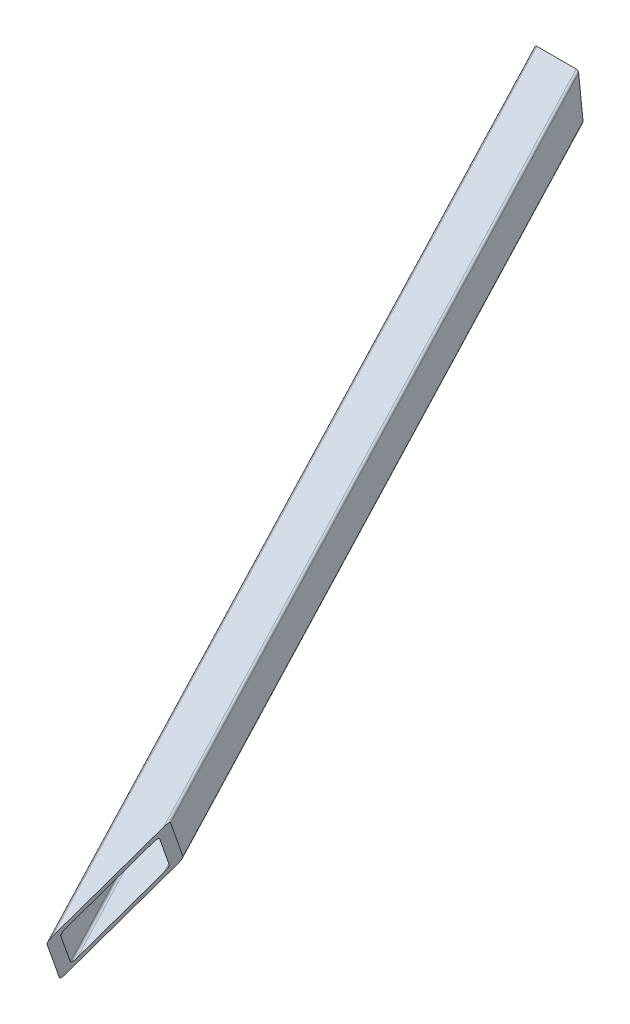
SolidWorks part; units mm, degrees
ref_plane "Plan de face" through (0, 0, 0) normal (0, 0, 1) x (1, 0, 0)
ref_plane "Plan de dessus" through (0, 0, 0) normal (0, 1, 0) x (1, 0, 0)
ref_plane "Plan de droite" through (0, 0, 0) normal (1, 0, 0) x (0, 0, -1)
sketch "Esquisse1" plane through (0, 0, 0) normal (0, 0, 1) x (1, 0, 0)
  line L0 (0, 0) -> (258, 0)
  line L1 (258, 0) -> (0, 256)
  line L2 (0, 256) -> (0, 0)
  dimension "D1" = 258
  dimension "D2" = 256
extrude "Boss.-Extru.1" add sketch "Esquisse1" along normal blind 729
sketch "Esquisse2" plane through (0, 0, 0) normal (-1, 0, 0) x (0, 0, 1)
  line L0 (0, 256) -> (729, 0)
  line L1 (729, 256) -> (0, 256) construction
  line L2 (0, 256) -> (0, 0) construction
  line L3 (729, 0) -> (729, 256)
  line L4 (729, 256) -> (0, 256)
extrude "Enlèv. mat.-Extru.1" cut sketch "Esquisse2" against normal blind 727
ref_plane "Plan1" through (0, 256, 0) normal (0.3167, -0.3143, 0.8949) x (0.9485, 0.1052, -0.2987)
sketch "Esquisse3" plane through (0, 256, 0) normal (0.3167, -0.3143, 0.8949) x (0.9485, 0.1052, -0.2987)
  line L1 (0, 0) -> (40, 0)
  line L2 (0, 0) -> (0, -40)
  line L3 (0, -40) -> (40, -40)
  line L4 (40, 0) -> (40, -40)
  dimension "D1" = 40
  dimension "D2" = 40
extrude "Boss.-Extru.2" add sketch "Esquisse3" along normal up to vertex (814.5803 mm away) up to point (258, 0, 729)
sketch "Esquisse4" plane through (0, 0, 0) normal (0, -1, 0) x (-1, 0, 0)
  line L1 (-258, -729) -> (-356.5784, -729)
  line L2 (-258, -729) -> (-258, -581.0499)
  line L3 (-258, -581.0499) -> (-356.5784, -581.0499)
  line L4 (-356.5784, -729) -> (-356.5784, -581.0499)
  line L5 (0, 0) -> (-77.8409, 0)
  line L6 (0, 0) -> (0, 46.0841)
  line L7 (0, 46.0841) -> (-77.8409, 46.0841)
  line L8 (-77.8409, 0) -> (-77.8409, 46.0841)
extrude "Enlèv. mat.-Extru.2" cut sketch "Esquisse4" against normal through all both and the other way through all
sketch "Esquisse7" plane through (0, 256, 0) normal (0.3167, -0.3143, 0.8949) x (0.9485, 0.1052, -0.2987)
  line L1 (40, 0) -> (0, 0)
  line L2 (40, 0) -> (40, -40)
  line L3 (40, -40) -> (0, -40)
  line L4 (0, 0) -> (0, -40)
  line L5 (433.6794, -362.0503) -> (-387.8651, -362.0503)
  line L6 (433.6794, -362.0503) -> (433.6794, 254.1081)
  line L7 (433.6794, 254.1081) -> (-387.8651, 254.1081)
  line L8 (-387.8651, -362.0503) -> (-387.8651, 254.1081)
extrude "Enlèv. mat.-Extru.6" cut sketch "Esquisse7" along normal through all
sketch "Esquisse8" plane through (0, 256, 0) normal (0.3167, -0.3143, 0.8949) x (0.9485, 0.1052, -0.2987)
  line L1 (0, 0) -> (40, 0) construction
  line L2 (0, 0) -> (0, -40) construction
  line L3 (0, -40) -> (40, -40) construction
  line L4 (40, 0) -> (40, -40) construction
  line L5 (40, 0) -> (40, -40) construction
  line L7 (4, -36) -> (36, -36)
  line L8 (36, -4) -> (36, -36)
  line L9 (4, -4) -> (36, -4)
  line L10 (4, -4) -> (4, -36)
  line L11 (40, -40) -> (0, -40) construction
  line L12 (0, -40) -> (0, 0) construction
  line L13 (40, -40) -> (0, -40) construction
  line L14 (0, 0) -> (40, 0) construction
  line L15 (40, 0) -> (40, -40) construction
  dimension "D1" = 4
extrude "Enlèv. mat.-Extru.9" cut sketch "Esquisse8" along normal through all
fillet "Congé2" radius 2 8 edges at (152.4359, 108.8711, 298.28) (150.0849, 148.933, 304.9229) (131.351, 87.9381, 357.8572) (131.3436, 126.0871, 357.878) (148.2115, 142.8335, 310.2163) (150.0923, 110.784, 304.902) (133.2244, 94.0376, 352.5637) (129, 128, 364.5)
